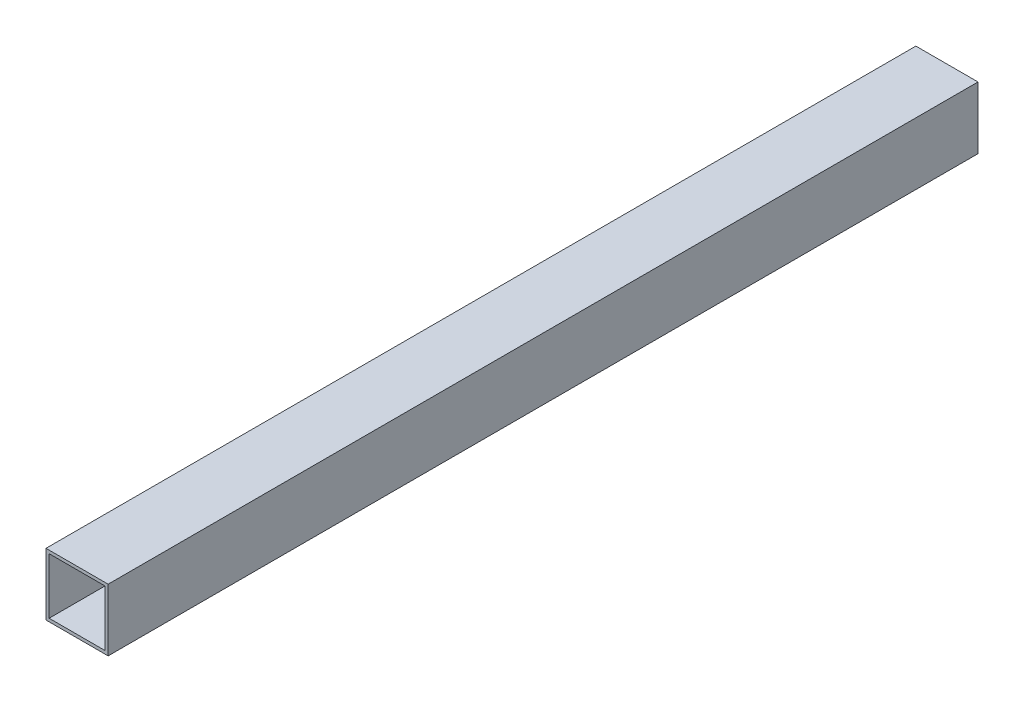
SolidWorks part; units mm, degrees
ref_plane "前视基准面" through (0, 0, 0) normal (0, 0, 1) x (1, 0, 0)
ref_plane "上视基准面" through (0, 0, 0) normal (0, 1, 0) x (1, 0, 0)
ref_plane "右视基准面" through (0, 0, 0) normal (1, 0, 0) x (0, 0, -1)
other "Configuration Table"
sketch "草图1" plane through (0, 0, 0) normal (0, 0, 1) x (1, 0, 0)
  line L0 (-6.5, 11.5) -> (11.5, 11.5)
  line L1 (-7.5, -7.5) -> (12.5, -7.5)
  line L2 (-7.5, -7.5) -> (-7.5, 12.5)
  line L3 (-7.5, 12.5) -> (12.5, 12.5)
  line L4 (12.5, -7.5) -> (12.5, 12.5)
  line L5 (11.5, -6.5) -> (11.5, 11.5)
  line L6 (-6.5, -6.5) -> (11.5, -6.5)
  line L7 (-6.5, -6.5) -> (-6.5, 11.5)
  point P0 (0, 0)
  dimension "D1" = 20
  dimension "D2" = 1
extrude "凸台-拉伸1" add sketch "草图1" along normal blind 280
